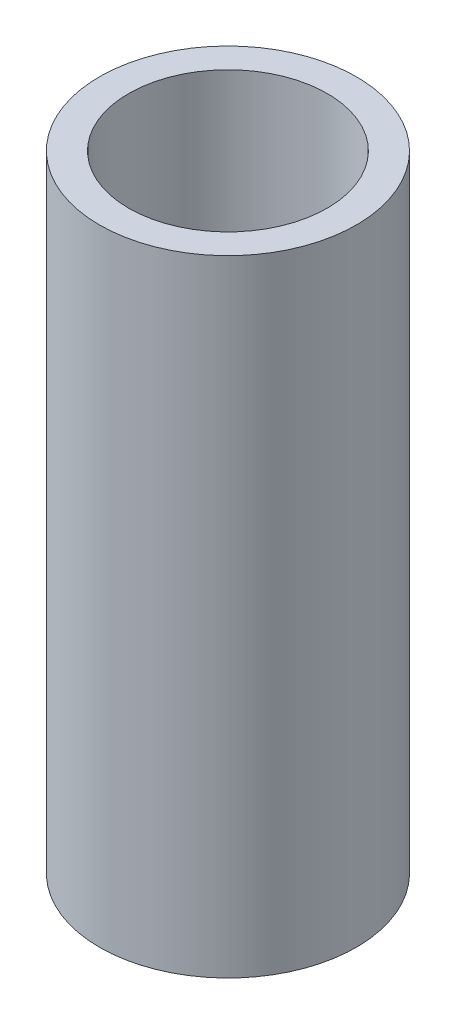
SolidWorks part; units mm, degrees
ref_plane "Front Plane" through (0, 0, 0) normal (0, 0, 1) x (1, 0, 0)
ref_plane "Top Plane" through (0, 0, 0) normal (0, 1, 0) x (1, 0, 0)
ref_plane "Right Plane" through (0, 0, 0) normal (1, 0, 0) x (0, 0, -1)
sketch "Sketch1" plane through (0.1219, -10.8842, 6.4001) normal (0, 1, 0) x (1, 0, 0)
  circle A0 centre (-0.1219, 6.4001) radius 5.1308
  dimension "D1" = 10.2616
extrude "Boss-Extrude1" add sketch "Sketch1" along normal blind 21.9964 and the other way blind 3
sketch "Sketch2" plane through (0, 11.1122, 0) normal (0, 1, 0) x (1, 0, 0)
  circle A0 centre (0, 0) radius 3.9688
  dimension "D1" = 7.9375
extrude "Cut-Extrude1" cut sketch "Sketch2" against normal blind 40
